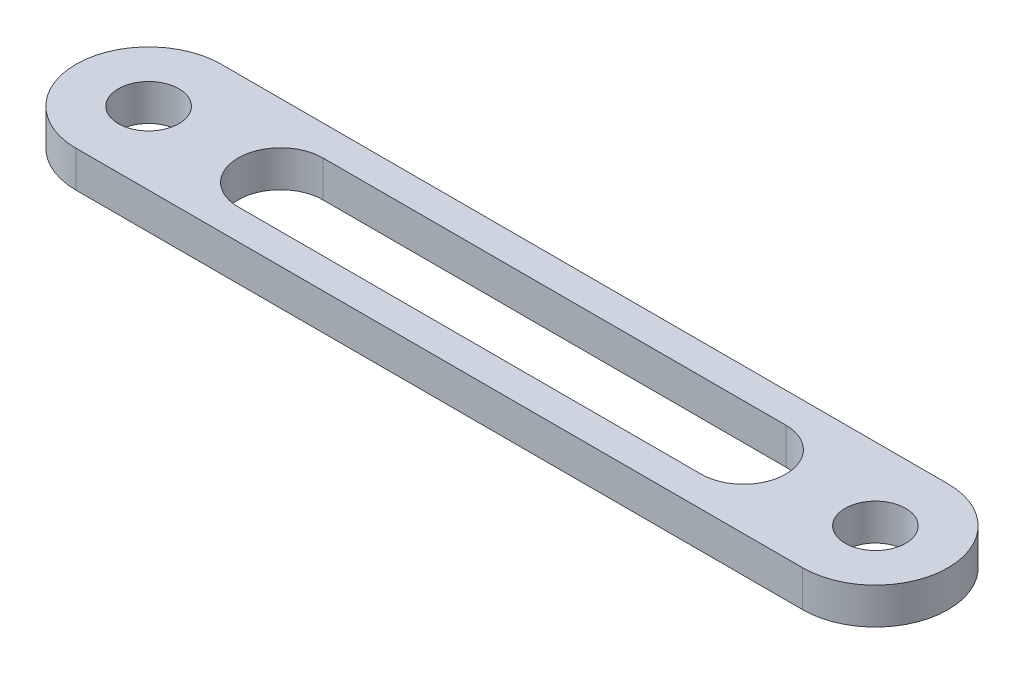
SolidWorks part; units mm, degrees
ref_plane "Front" through (0, 0, 0) normal (0, 0, 1) x (1, 0, 0)
ref_plane "Top" through (0, 0, 0) normal (0, 1, 0) x (1, 0, 0)
ref_plane "Right" through (0, 0, 0) normal (1, 0, 0) x (0, 0, -1)
sketch "Sketch1" plane through (0, 0, 0) normal (0, 1, 0) x (1, 0, 0)
  line L0 (38.1, 0) -> (-38.1, 0) construction
  line L1 (38.1, -7.62) -> (-38.1, -7.62)
  line L2 (38.1, 7.62) -> (-38.1, 7.62)
  line L3 (-24.2669, 0) -> (24.2669, 0) construction
  line L6 (-24.2669, 4.445) -> (24.2669, 4.445)
  line L7 (-24.2669, -4.445) -> (24.2669, -4.445)
  arc A0 (38.1, -7.62) -> (38.1, 7.62) centre (38.1, 0) ccw
  arc A1 (-38.1, 7.62) -> (-38.1, -7.62) centre (-38.1, 0) ccw
  circle A2 centre (-38.1, 0) radius 3.175
  circle A3 centre (38.1, 0) radius 3.175
  arc A4 (-24.2669, 4.445) -> (-24.2669, -4.445) centre (-24.2669, 0) ccw
  arc A5 (24.2669, -4.445) -> (24.2669, 4.445) centre (24.2669, 0) ccw
  point P2 (0, 0)
  point P14 (0, 0)
  dimension "D1" = 6.35
  dimension "D2" = 6.35
  dimension "D3" = 15.24
  dimension "D4" = 76.2
  dimension "D5" = 8.89
extrude "Boss-Extrude5" add sketch "Sketch1" along normal blind 3.81
